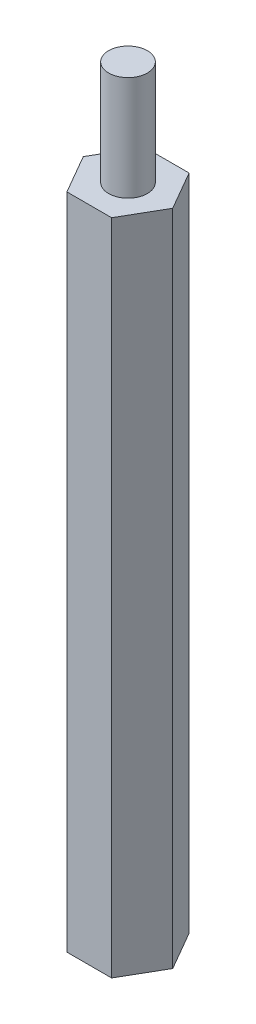
SolidWorks part; units mm, degrees
ref_plane "Front Plane" through (0, 0, 0) normal (0, 0, 1) x (1, 0, 0)
ref_plane "Top Plane" through (0, 0, 0) normal (0, 1, 0) x (1, 0, 0)
ref_plane "Right Plane" through (0, 0, 0) normal (1, 0, 0) x (0, 0, -1)
sketch "Sketch3" plane through (0, 0, 0) normal (0, 1, 0) x (1, 0, 0)
  line L1 (-3.4641, 0) -> (-1.7321, -3)
  line L2 (-1.7321, -3) -> (1.7321, -3)
  line L3 (1.7321, -3) -> (3.4641, 0)
  line L4 (3.4641, 0) -> (1.7321, 3)
  line L5 (1.7321, 3) -> (-1.7321, 3)
  line L6 (-1.7321, 3) -> (-3.4641, 0)
  circle A0 centre (0, 0) radius 3 construction
  dimension "D1" = 6
extrude "Boss-Extrude1" add sketch "Sketch3" along normal blind 51
sketch "Sketch5" plane through (0, 51, 0) normal (0, 1, 0) x (1, 0, 0)
  circle A0 centre (0, 0) radius 1.5
  dimension "D1" = 3
extrude "Boss-Extrude2" add sketch "Sketch5" along normal blind 8.0916
sketch "Sketch6" plane through (0, 0, 0) normal (0, -1, 0) x (1, 0, 0)
  circle A0 centre (0, 0) radius 1.5
extrude "Cut-Extrude1" cut sketch "Sketch6" against normal blind 4
